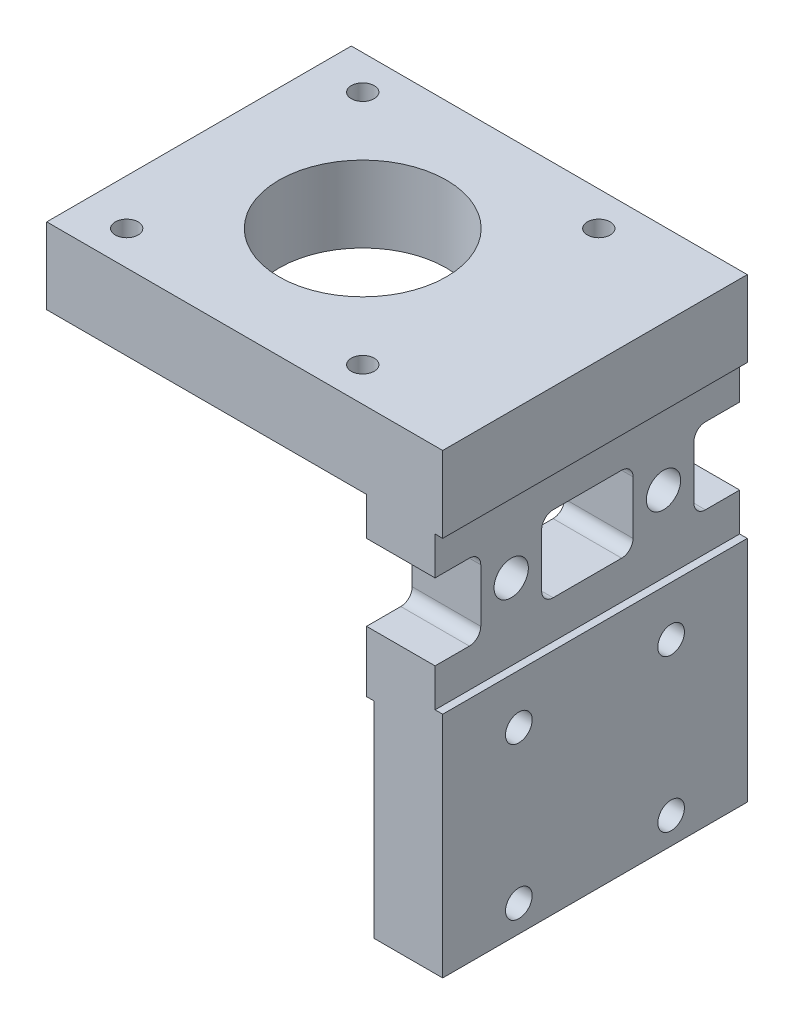
SolidWorks part; units mm, degrees
ref_plane "Front Plane" through (0, 0, 0) normal (0, 0, 1) x (1, 0, 0)
ref_plane "Top Plane" through (0, 0, 0) normal (0, 1, 0) x (1, 0, 0)
ref_plane "Right Plane" through (0, 0, 0) normal (1, 0, 0) x (0, 0, -1)
sketch "Sketch1" plane through (0, 0, 0) normal (1, 0, 0) x (0, 0, -1)
  line L1 (0, 51.8391) -> (40, 51.8391)
  line L2 (0, 51.8391) -> (0, 1.8391)
  line L3 (0, 1.8391) -> (40, 1.8391)
  line L4 (40, 51.8391) -> (40, 1.8391)
  dimension "D1" = 40
  dimension "D2" = 50
extrude "Boss-Extrude1" add sketch "Sketch1" along normal blind 10
sketch "Sketch2" plane through (0, 0, 0) normal (-1, 0, 0) x (0, 0, 1)
  line L0 (-40, 1.8391) -> (-40, 51.8391) construction
  line L1 (-40, 28.8391) -> (0, 28.8391)
  line L2 (-40, 28.8391) -> (-40, 1.8391)
  line L3 (-40, 1.8391) -> (0, 1.8391)
  line L4 (0, 28.8391) -> (0, 1.8391)
  dimension "D1" = 27
extrude "Cut-Extrude1" cut sketch "Sketch2" against normal blind 1
sketch "Sketch3" plane through (10, 0, 0) normal (1, 0, 0) x (0, 0, -1)
  line L0 (0, 1.8391) -> (40, 1.8391) construction
  line L1 (40, 1.8391) -> (40, 51.8391) construction
  line L2 (0, 51.8391) -> (0, 1.8391) construction
  circle A0 centre (10, 25.3391) radius 1.75
  circle A1 centre (30, 25.3391) radius 1.75
  circle A2 centre (30, 5.3391) radius 1.75
  circle A3 centre (10, 5.3391) radius 1.75
  dimension "D1" = 3.5
  dimension "D2" = 3.5
  dimension "D3" = 20
  dimension "D4" = 3.5
  dimension "D5" = 3.5
  dimension "D6" = 3.5
  dimension "D7" = 3.5
  dimension "D8" = 20
  dimension "D9" = 20
  dimension "D10" = 10
  dimension "D11" = 10
  dimension "D12" = 20
extrude "Cut-Extrude2" cut sketch "Sketch3" against normal blind 10
sketch "Sketch4" plane through (10, 0, 0) normal (1, 0, 0) x (0, 0, -1)
  line L0 (40, 1.8391) -> (40, 51.8391) construction
  line L1 (0, 51.8391) -> (40, 51.8391)
  line L2 (0, 51.8391) -> (0, 31.8391)
  line L3 (0, 31.8391) -> (40, 31.8391)
  line L4 (40, 51.8391) -> (40, 31.8391)
  dimension "D1" = 20
extrude "Cut-Extrude3" cut sketch "Sketch4" against normal blind 1
sketch "Sketch6" plane through (0, 0, 0) normal (-1, 0, 0) x (0, 0, 1)
  line L0 (0, 51.8391) -> (0, 28.8391) construction
  line L1 (-40, 51.8391) -> (0, 51.8391) construction
  circle A0 centre (-30, 41.8391) radius 2.25
  circle A1 centre (-10, 41.8391) radius 2.25
  dimension "D1" = 4.5
  dimension "D2" = 4.5
  dimension "D3" = 20
  dimension "D4" = 10
  dimension "D5" = 10
  dimension "D6" = 10
extrude "Cut-Extrude4" cut sketch "Sketch6" against normal blind 10
sketch "Sketch7" plane through (0, 51.8391, 0) normal (0, 1, 0) x (1, 0, 0)
  line L1 (10, 40) -> (-42, 40)
  line L2 (10, 40) -> (10, 0)
  line L3 (10, 0) -> (-42, 0)
  line L4 (-42, 40) -> (-42, 0)
  dimension "D1" = 52
extrude "Boss-Extrude2" add sketch "Sketch7" along normal blind 10
sketch "Sketch8" plane through (0, 61.8391, 0) normal (0, 1, 0) x (1, 0, 0)
  line L2 (10, 40) -> (-42, 40) construction
  line L4 (-42, 40) -> (-42, 0) construction
  circle A0 centre (-20.5, 20) radius 11
  dimension "D1" = 20
  dimension "D2" = 21.5
  dimension "D3" = 22
extrude "Cut-Extrude5" cut sketch "Sketch8" against normal blind 10
sketch "Sketch9" plane through (9, 0, 0) normal (1, 0, 0) x (0, 0, -1)
  line L0 (40, 31.8391) -> (40, 51.8391) construction
  line L1 (34, 46.8391) -> (40, 46.8391)
  line L2 (34, 46.8391) -> (34, 36.8391)
  line L3 (34, 36.8391) -> (40, 36.8391)
  line L4 (40, 46.8391) -> (40, 36.8391)
  line L5 (0, 31.8391) -> (40, 31.8391) construction
  line L6 (40, 51.8391) -> (0, 51.8391) construction
  line L7 (0, 31.8391) -> (40, 31.8391) construction
  line L8 (14, 46.8391) -> (26, 46.8391)
  line L9 (14, 46.8391) -> (14, 36.8391)
  line L10 (14, 36.8391) -> (26, 36.8391)
  line L11 (26, 46.8391) -> (26, 36.8391)
  line L12 (0, 51.8391) -> (40, 51.8391) construction
  line L13 (0, 51.8391) -> (0, 31.8391) construction
  line L15 (0, 46.8391) -> (6, 46.8391)
  line L16 (0, 46.8391) -> (0, 36.8391)
  line L17 (0, 36.8391) -> (6, 36.8391)
  line L18 (6, 46.8391) -> (6, 36.8391)
  dimension "D1" = 6
  dimension "D2" = 5
  dimension "D3" = 5
  dimension "D4" = 5
  dimension "D5" = 5
  dimension "D6" = 14
  dimension "D7" = 14
  dimension "D8" = 5
  dimension "D9" = 5
  dimension "D10" = 6
extrude "Cut-Extrude6" cut sketch "Sketch9" against normal blind 10
sketch "Sketch10" plane through (0, 61.8391, 0) normal (0, 1, 0) x (1, 0, 0)
  circle A0 centre (-36, 35.5) radius 1.5
  circle A1 centre (-5, 35.5) radius 1.5
  circle A2 centre (-5, 4.5) radius 1.5
  circle A3 centre (-36, 4.5) radius 1.5
  circle A4 centre (-20.5, 20) radius 11 construction
  dimension "D1" = 3
  dimension "D2" = 3
  dimension "D3" = 3
  dimension "D4" = 3
  dimension "D5" = 31
  dimension "D6" = 31
  dimension "D7" = 31
  dimension "D8" = 31
  dimension "D9" = 15.5
  dimension "D10" = 15.5
  dimension "D11" = 15.5
extrude "Cut-Extrude7" cut sketch "Sketch10" against normal blind 10
fillet "Fillet1" radius 1.5 4 edges at (4.5, 36.8391, -14) (4.5, 36.8391, -26) (4.5, 46.8391, -26) (4.5, 46.8391, -14)
fillet "Fillet2" radius 1.5 4 edges at (4.5, 46.8391, -34) (4.5, 36.8391, -34) (4.5, 36.8391, -6) (4.5, 46.8391, -6)
